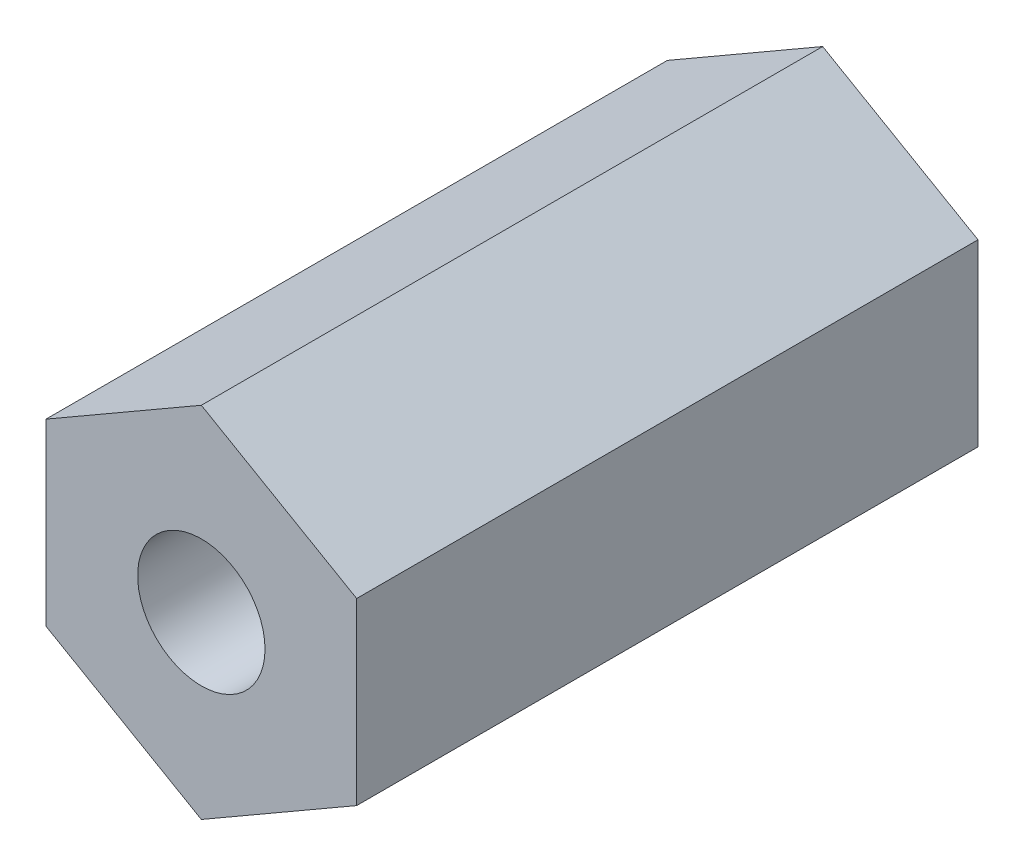
SolidWorks part; units mm, degrees
material "Latón"
ref_plane "Alzado" through (0, 0, 0) normal (0, 0, 1) x (1, 0, 0)
ref_plane "Planta" through (0, 0, 0) normal (0, 1, 0) x (1, 0, 0)
ref_plane "Vista lateral" through (0, 0, 0) normal (1, 0, 0) x (0, 0, -1)
sketch "Sk_Cuerpo" plane through (0, 0, 0) normal (0, 0, 1) x (1, 0, 0)
  line L1 (0, -2.8868) -> (2.5, -1.4434)
  line L2 (2.5, -1.4434) -> (2.5, 1.4434)
  line L3 (2.5, 1.4434) -> (0, 2.8868)
  line L4 (0, 2.8868) -> (-2.5, 1.4434)
  line L5 (-2.5, 1.4434) -> (-2.5, -1.4434)
  line L6 (-2.5, -1.4434) -> (0, -2.8868)
  circle A0 centre (0, 0) radius 2.5 construction
  dimension "D1" = 5
extrude "Cuerpo" add sketch "Sk_Cuerpo" along normal blind 10
sketch "Sk_Rosca_pasante" plane through (0, 0, 0) normal (0, 0, 1) x (1, 0, 0)
  circle A0 centre (0, 0) radius 1.025
  dimension "D1" = 2.05
extrude "Rosca_pasante" cut sketch "Sk_Rosca_pasante" along normal blind 10
